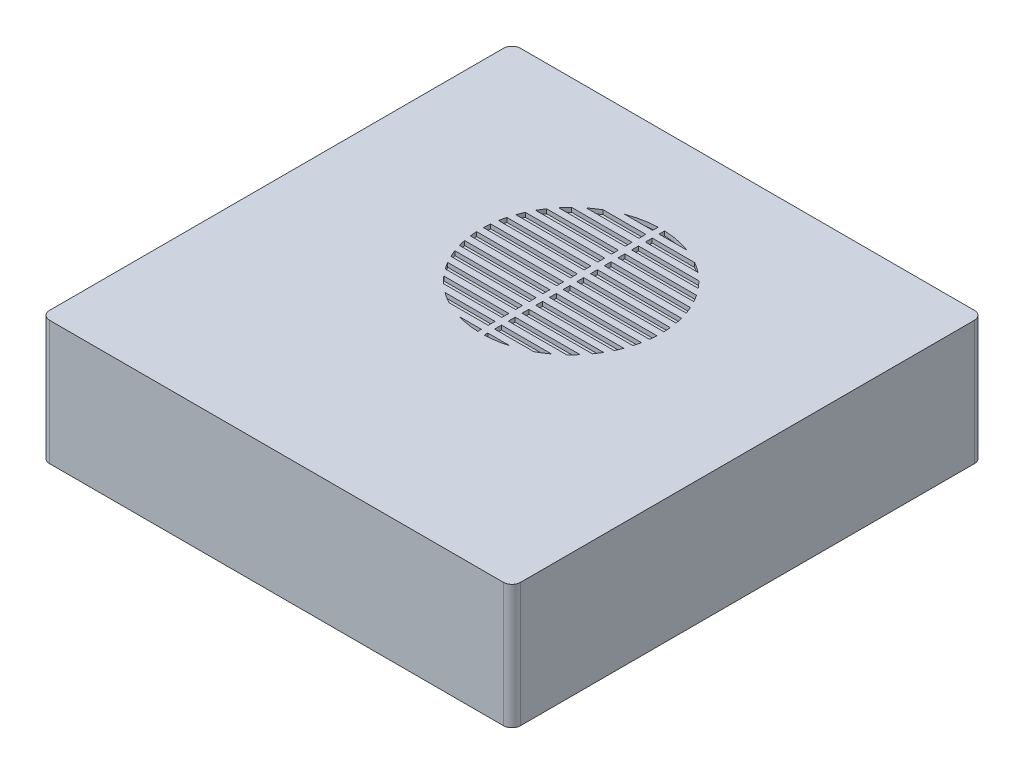
SolidWorks part; units mm, degrees
ref_plane "前视基准面" through (0, 0, 0) normal (0, 0, 1) x (1, 0, 0)
ref_plane "上视基准面" through (0, 0, 0) normal (0, 1, 0) x (1, 0, 0)
ref_plane "右视基准面" through (0, 0, 0) normal (1, 0, 0) x (0, 0, -1)
sketch "草图1" plane through (0, 0, 0) normal (0, 1, 0) x (1, 0, 0)
  line L1 (55, -55) -> (-55, -55)
  line L2 (55, -55) -> (55, 55)
  line L3 (55, 55) -> (-55, 55)
  line L4 (-55, -55) -> (-55, 55)
  line L5 (55, -55) -> (-55, 55) construction
  line L6 (55, 55) -> (-55, -55) construction
  point P0 (0, 0)
extrude "凸台-拉伸1" add sketch "草图1" along normal blind 29
sketch "草图2" plane through (0, 29, 0) normal (0, 1, 0) x (1, 0, 0)
  line L0 (-0.7519, 34.8863) -> (-0.7519, 33.5915)
  line L1 (-0.7519, 31.9915) -> (-0.7519, 30.3915)
  line L2 (0.7519, 34.8863) -> (0.7519, 33.5915)
  line L3 (-7.3108, 33.5915) -> (-0.7519, 33.5915)
  line L4 (-10.6846, 31.9915) -> (-0.7519, 31.9915)
  line L5 (-13.029, 30.3915) -> (-0.7519, 30.3915)
  line L6 (-14.8401, 28.7915) -> (-0.7519, 28.7915)
  line L7 (-16.2967, 27.1915) -> (-0.7519, 27.1915)
  line L8 (-17.4876, 25.5915) -> (-0.7519, 25.5915)
  line L9 (-18.4643, 23.9915) -> (-0.7519, 23.9915)
  line L10 (-19.2594, 22.3915) -> (-0.7519, 22.3915)
  line L11 (-19.8947, 20.7915) -> (-0.7519, 20.7915)
  line L12 (-20.3851, 19.1915) -> (-0.7519, 19.1915)
  line L13 (-20.7409, 17.5915) -> (-0.7519, 17.5915)
  line L14 (-20.969, 15.9915) -> (-0.7519, 15.9915)
  line L15 (-21.0735, 14.3915) -> (-0.7519, 14.3915)
  line L16 (-21.0563, 12.7915) -> (-0.7519, 12.7915)
  line L17 (-20.917, 11.1915) -> (-0.7519, 11.1915)
  line L18 (-20.6532, 9.5915) -> (-0.7519, 9.5915)
  line L19 (-20.2601, 7.9915) -> (-0.7519, 7.9915)
  line L20 (-19.7298, 6.3915) -> (-0.7519, 6.3915)
  line L21 (-19.0509, 4.7915) -> (-0.7519, 4.7915)
  line L22 (-18.2069, 3.1915) -> (-0.7519, 3.1915)
  line L23 (-17.1734, 1.5915) -> (-0.7519, 1.5915)
  line L24 (-15.9135, -0.0085) -> (-0.7519, -0.0085)
  line L25 (-14.3678, -1.6085) -> (-0.7519, -1.6085)
  line L26 (-12.4301, -3.2085) -> (-0.7519, -3.2085)
  line L27 (-9.8722, -4.8085) -> (-0.7519, -4.8085)
  line L28 (-5.941, -6.4085) -> (-0.7519, -6.4085)
  line L29 (0.7519, 31.9915) -> (0.7519, 30.3915)
  line L30 (0.7519, 28.7915) -> (0.7519, 27.1915)
  line L31 (0.7519, 33.5915) -> (7.3108, 33.5915)
  line L32 (0.7519, 31.9915) -> (10.6846, 31.9915)
  line L33 (0.7519, 30.3915) -> (13.029, 30.3915)
  line L34 (0.7519, 28.7915) -> (14.8401, 28.7915)
  line L35 (0.7519, 27.1915) -> (16.2967, 27.1915)
  line L36 (0.7519, 25.5915) -> (17.4876, 25.5915)
  line L37 (0.7519, 23.9915) -> (18.4643, 23.9915)
  line L38 (0.7519, 22.3915) -> (19.2594, 22.3915)
  line L39 (0.7519, 20.7915) -> (19.8947, 20.7915)
  line L40 (0.7519, 19.1915) -> (20.3851, 19.1915)
  line L41 (0.7519, 17.5915) -> (20.7409, 17.5915)
  line L42 (0.7519, 15.9915) -> (20.969, 15.9915)
  line L43 (0.7519, 14.3915) -> (21.0735, 14.3915)
  line L44 (0.7519, 12.7915) -> (21.0563, 12.7915)
  line L45 (0.7519, 11.1915) -> (20.917, 11.1915)
  line L46 (0.7519, 9.5915) -> (20.6532, 9.5915)
  line L47 (0.7519, 7.9915) -> (20.2601, 7.9915)
  line L48 (0.7519, 6.3915) -> (19.7298, 6.3915)
  line L49 (0.7519, 4.7915) -> (19.0509, 4.7915)
  line L50 (0.7519, 3.1915) -> (18.2069, 3.1915)
  line L51 (0.7519, 1.5915) -> (17.1734, 1.5915)
  line L52 (0.7519, -0.0085) -> (15.9135, -0.0085)
  line L53 (0.7519, -1.6085) -> (14.3678, -1.6085)
  line L54 (0.7519, -3.2085) -> (12.4301, -3.2085)
  line L55 (0.7519, -4.8085) -> (9.8722, -4.8085)
  line L56 (0.7519, -6.4085) -> (5.941, -6.4085)
  line L58 (-0.7519, 28.7915) -> (-0.7519, 27.1915)
  line L59 (-0.7519, 25.5915) -> (-0.7519, 23.9915)
  line L60 (0.7519, 25.5915) -> (0.7519, 23.9915)
  line L61 (0.7519, 22.3915) -> (0.7519, 20.7915)
  line L62 (-0.7519, 22.3915) -> (-0.7519, 20.7915)
  line L63 (-0.7519, 19.1915) -> (-0.7519, 17.5915)
  line L64 (0.7519, 19.1915) -> (0.7519, 17.5915)
  line L65 (-0.7519, 15.9915) -> (-0.7519, 14.3915)
  line L66 (0.7519, 15.9915) -> (0.7519, 14.3915)
  line L67 (-0.7519, 12.7915) -> (-0.7519, 11.1915)
  line L68 (0.7519, 12.7915) -> (0.7519, 11.1915)
  line L69 (-0.7519, 9.5915) -> (-0.7519, 7.9915)
  line L70 (0.7519, 9.5915) -> (0.7519, 7.9915)
  line L71 (-0.7519, 6.3915) -> (-0.7519, 4.7915)
  line L72 (0.7519, 6.3915) -> (0.7519, 4.7915)
  line L73 (-0.7519, 3.1915) -> (-0.7519, 1.5915)
  line L74 (0.7519, 3.1915) -> (0.7519, 1.5915)
  line L75 (-0.7519, -0.0085) -> (-0.7519, -1.6085)
  line L76 (0.7519, -0.0085) -> (0.7519, -1.6085)
  line L77 (0.7519, -3.2085) -> (0.7519, -4.8085)
  line L78 (-0.7519, -3.2085) -> (-0.7519, -4.8085)
  line L79 (0.7519, -6.4085) -> (0.7519, -7.2495)
  line L80 (-0.7519, -6.4085) -> (-0.7519, -7.2495)
  arc A0 (7.3108, 33.5915) -> (0.7519, 34.8863) centre (0, 13.8184) ccw
  arc A1 (-10.6846, 31.9915) -> (-13.029, 30.3915) centre (0, 13.8184) ccw
  arc A2 (13.029, 30.3915) -> (10.6846, 31.9915) centre (0, 13.8184) ccw
  arc A3 (-14.8401, 28.7915) -> (-16.2967, 27.1915) centre (0, 13.8184) ccw
  arc A4 (-17.4876, 25.5915) -> (-18.4643, 23.9915) centre (0, 13.8184) ccw
  arc A5 (16.2967, 27.1915) -> (14.8401, 28.7915) centre (0, 13.8184) ccw
  arc A6 (18.4643, 23.9915) -> (17.4876, 25.5915) centre (0, 13.8184) ccw
  arc A7 (-19.2594, 22.3915) -> (-19.8947, 20.7915) centre (0, 13.8184) ccw
  arc A8 (-20.3851, 19.1915) -> (-20.7409, 17.5915) centre (0, 13.8184) ccw
  arc A9 (19.8947, 20.7915) -> (19.2594, 22.3915) centre (0, 13.8184) ccw
  arc A10 (9.8722, -4.8085) -> (12.4301, -3.2085) centre (0, 13.8184) ccw
  arc A11 (14.3678, -1.6085) -> (15.9135, -0.0085) centre (0, 13.8184) ccw
  arc A12 (17.1734, 1.5915) -> (18.2069, 3.1915) centre (0, 13.8184) ccw
  arc A13 (19.0509, 4.7915) -> (19.7298, 6.3915) centre (0, 13.8184) ccw
  arc A14 (20.2601, 7.9915) -> (20.6532, 9.5915) centre (0, 13.8184) ccw
  arc A15 (20.917, 11.1915) -> (21.0563, 12.7915) centre (0, 13.8184) ccw
  arc A16 (21.0735, 14.3915) -> (20.969, 15.9915) centre (0, 13.8184) ccw
  arc A17 (20.7409, 17.5915) -> (20.3851, 19.1915) centre (0, 13.8184) ccw
  arc A18 (-20.969, 15.9915) -> (-21.0735, 14.3915) centre (0, 13.8184) ccw
  arc A19 (-21.0563, 12.7915) -> (-20.917, 11.1915) centre (0, 13.8184) ccw
  arc A20 (-20.6532, 9.5915) -> (-20.2601, 7.9915) centre (0, 13.8184) ccw
  arc A21 (-19.7298, 6.3915) -> (-19.0509, 4.7915) centre (0, 13.8184) ccw
  arc A22 (-18.2069, 3.1915) -> (-17.1734, 1.5915) centre (0, 13.8184) ccw
  arc A23 (-15.9135, -0.0085) -> (-14.3678, -1.6085) centre (0, 13.8184) ccw
  arc A24 (-12.4301, -3.2085) -> (-9.8722, -4.8085) centre (0, 13.8184) ccw
  arc A25 (-5.941, -6.4085) -> (-0.7519, -7.2495) centre (0, 13.8184) ccw
  arc A26 (0.7519, -7.2495) -> (5.941, -6.4085) centre (0, 13.8184) ccw
  arc A27 (-0.7519, 34.8863) -> (-7.3108, 33.5915) centre (0, 13.8184) ccw
  dimension "D1" = 26
extrude "切除-拉伸1" cut sketch "草图2" against normal blind 7
sketch "草图3" plane through (0, 22, 0) normal (0, 1, 0) x (1, 0, 0)
  line L0 (-0.7519, 15.9915) -> (-20.969, 15.9915) construction
  line L1 (24.4959, 44.0277) -> (-29.3881, 44.0277)
  line L2 (24.4959, 44.0277) -> (24.4959, -12.0447)
  line L3 (24.4959, -12.0447) -> (-29.3881, -12.0447)
  line L4 (-29.3881, 44.0277) -> (-29.3881, -12.0447)
  line L5 (24.4959, 44.0277) -> (-29.3881, -12.0447) construction
  line L6 (24.4959, -12.0447) -> (-29.3881, 44.0277) construction
  point P0 (-2.4461, 15.9915)
extrude "切除-拉伸3" cut sketch "草图3" along normal blind 6
sketch "草图4" plane through (0, 0, -55) normal (0, 0, -1) x (-1, 0, 0)
  line L1 (-48.8726, 8.0011) -> (-38.5493, 8.0011)
  line L2 (-48.8726, 8.0011) -> (-48.8726, 4.4022)
  line L3 (-48.8726, 4.4022) -> (-38.5493, 4.4022)
  line L4 (-38.5493, 8.0011) -> (-38.5493, 4.4022)
  line L5 (-33.0562, 8.0011) -> (-22.2593, 8.0011)
  line L6 (-33.0562, 8.0011) -> (-33.0562, 4.4022)
  line L7 (-33.0562, 4.4022) -> (-22.2593, 4.4022)
  line L8 (-22.2593, 8.0011) -> (-22.2593, 4.4022)
  line L9 (-17.5239, 8.0011) -> (-6.2535, 8.0011)
  line L10 (-17.5239, 8.0011) -> (-17.5239, 4.4022)
  line L11 (-17.5239, 4.4022) -> (-6.2535, 4.4022)
  line L12 (-6.2535, 8.0011) -> (-6.2535, 4.4022)
  line L13 (-0.0974, 12.0736) -> (49.0567, 12.0736)
  line L14 (-0.0974, 12.0736) -> (-0.0974, 4.4022)
  line L15 (-0.0974, 4.4022) -> (49.0567, 4.4022)
  line L16 (49.0567, 12.0736) -> (49.0567, 4.4022)
extrude "切除-拉伸4" cut sketch "草图4" against normal blind 10
fillet "圆角1" radius 2 4 edges at (55, 14.5, 55) (-55, 14.5, 55) (-55, 14.5, -55) (55, 14.5, -55)
